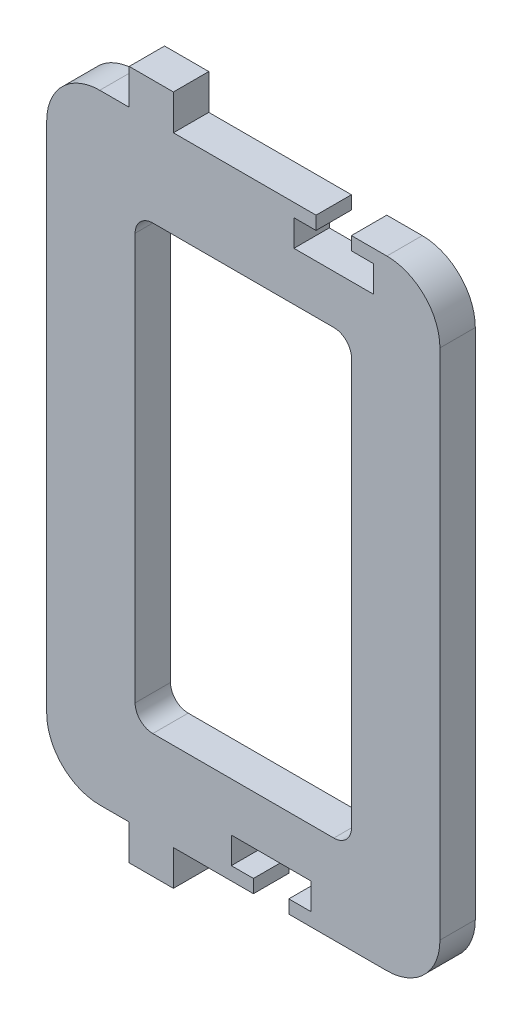
SolidWorks part; units mm, degrees
ref_plane "Alzado" through (0, 0, 0) normal (0, 0, 1) x (1, 0, 0)
ref_plane "Planta" through (0, 0, 0) normal (0, 1, 0) x (1, 0, 0)
ref_plane "Vista lateral" through (0, 0, 0) normal (1, 0, 0) x (0, 0, -1)
sketch "Croquis1" plane through (0, 0, 0) normal (0, 0, 1) x (1, 0, 0)
  line L0 (-48.3652, -20.8541) -> (-51.6952, -20.8541)
  line L1 (-48.3652, -20.8541) -> (-48.3652, -24.8541)
  line L2 (-48.3652, -24.8541) -> (-43.3652, -24.8541)
  line L3 (-43.3652, -24.8541) -> (-43.3652, -20.8541)
  line L4 (-43.3652, -20.8541) -> (-34.3152, -20.8541)
  line L5 (-34.3152, -20.8541) -> (-34.3152, -19.3541)
  line L6 (-34.3152, -19.3541) -> (-36.8152, -19.3541)
  line L7 (-36.8152, -19.3541) -> (-36.8152, -16.3541)
  line L8 (-27.8152, -16.3541) -> (-36.8152, -16.3541)
  line L9 (-27.8152, -16.3541) -> (-27.8152, -19.3541)
  line L10 (-27.8152, -19.3541) -> (-30.3152, -19.3541)
  line L11 (-30.3152, -19.3541) -> (-30.3152, -20.8541)
  line L12 (-20.7352, 44.6459) -> (-29.7352, 44.6459)
  line L13 (-30.3152, -20.8541) -> (-19.2252, -20.8541)
  line L14 (-13.2252, -14.8541) -> (-13.2252, 43.1459)
  line L15 (-57.6952, -14.8541) -> (-57.6952, 43.1459)
  line L16 (-48.3652, 49.1459) -> (-48.3652, 53.1459)
  line L17 (-48.3652, 53.1459) -> (-43.3652, 53.1459)
  line L18 (-43.3652, 53.1459) -> (-43.3652, 49.1459)
  line L19 (-43.3652, 49.1459) -> (-27.2352, 49.1459)
  line L20 (-27.2352, 49.1459) -> (-27.2352, 47.6459)
  line L21 (-27.2352, 47.6459) -> (-29.7352, 47.6459)
  line L22 (-29.7352, 47.6459) -> (-29.7352, 44.6459)
  line L24 (-20.7352, 44.6459) -> (-20.7352, 47.6459)
  line L25 (-20.7352, 47.6459) -> (-23.2352, 47.6459)
  line L26 (-23.2352, 47.6459) -> (-23.2352, 49.1459)
  line L27 (-23.2352, 49.1459) -> (-19.2252, 49.1459)
  line L28 (-51.6952, 49.1459) -> (-48.3652, 49.1459)
  line L33 (-47.6952, 14.1459) -> (-47.6952, -8.8541)
  line L34 (-45.6952, -10.8541) -> (-25.2252, -10.8541)
  line L35 (-23.2252, -8.8541) -> (-23.2252, 37.1459)
  line L36 (-25.2252, 39.1459) -> (-45.6952, 39.1459)
  line L37 (-47.6952, 37.1459) -> (-47.6952, 14.1459)
  arc A0 (-51.6952, -20.8541) -> (-57.6952, -14.8541) centre (-51.6952, -14.8541) cw
  arc A1 (-19.2252, -20.8541) -> (-13.2252, -14.8541) centre (-19.2252, -14.8541) ccw
  arc A2 (-13.2252, 43.1459) -> (-19.2252, 49.1459) centre (-19.2252, 43.1459) ccw
  arc A3 (-57.6952, 43.1459) -> (-51.6952, 49.1459) centre (-51.6952, 43.1459) cw
  arc A4 (-25.2252, -10.8541) -> (-23.2252, -8.8541) centre (-25.2252, -8.8541) ccw
  arc A5 (-23.2252, 37.1459) -> (-25.2252, 39.1459) centre (-25.2252, 37.1459) ccw
  arc A6 (-45.6952, 39.1459) -> (-47.6952, 37.1459) centre (-45.6952, 37.1459) ccw
  arc A7 (-47.6952, -8.8541) -> (-45.6952, -10.8541) centre (-45.6952, -8.8541) ccw
  point P47 (-8.5252, 49.1459)
  dimension "D1" = 6
  dimension "D2" = 2
extrude "Saliente-Extruir1" add sketch "Croquis1" along normal blind 4
